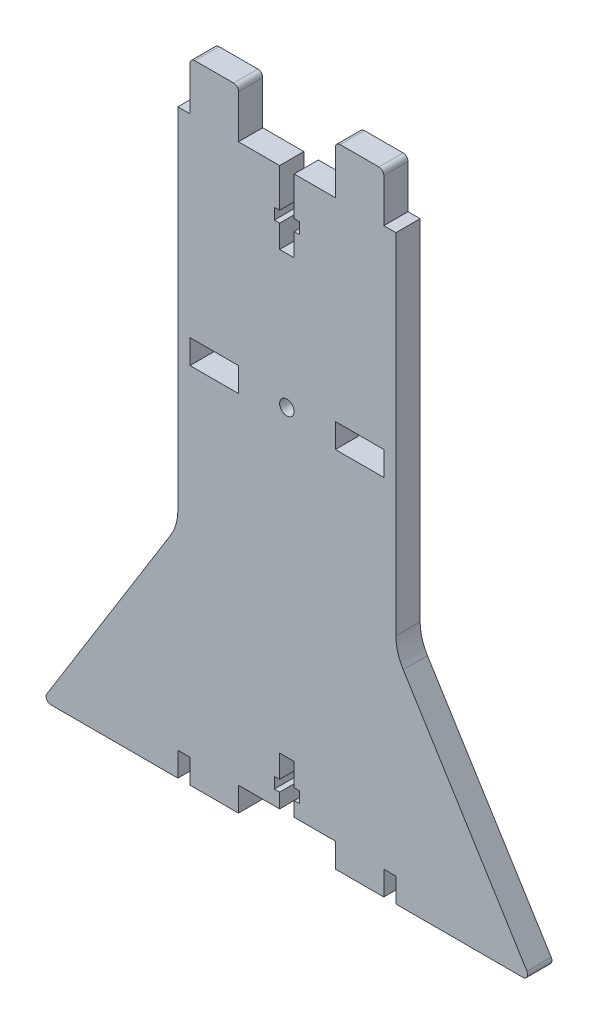
SolidWorks part; units mm, degrees
ref_plane "Front Plane" through (0, 0, 0) normal (0, 0, 1) x (1, 0, 0)
ref_plane "Top Plane" through (0, 0, 0) normal (0, 1, 0) x (1, 0, 0)
ref_plane "Right Plane" through (0, 0, 0) normal (1, 0, 0) x (0, 0, -1)
sketch "Sketch1" plane through (0, 0, 0) normal (0, 0, 1) x (1, 0, 0)
  line L1 (-32.5189, -56.1915) -> (-30.0189, -56.1915)
  line L2 (-30.0189, -56.1915) -> (-30.0189, -61.1915)
  line L3 (-30.0189, -61.1915) -> (-20.0189, -61.1915)
  line L4 (-20.0189, -61.1915) -> (-20.0189, -56.1915)
  line L6 (-0.0189, -56.1915) -> (-0.0189, -61.1915)
  line L7 (-0.0189, -61.1915) -> (9.9811, -61.1915)
  line L8 (9.9811, -61.1915) -> (9.9811, -56.1915)
  line L9 (9.9811, -56.1915) -> (12.4811, -56.1915)
  line L12 (-38.5749, -16.1038) -> (31.2699, -16.1038) construction
  line L13 (-11.5189, -56.1915) -> (-8.5189, -56.1915) construction
  line L14 (-8.5189, -56.1915) -> (-8.5189, -53.1915)
  line L15 (-8.5189, -50.8915) -> (-7.4189, -50.8915)
  line L16 (-12.6189, -53.1915) -> (-12.6189, -50.8915)
  line L17 (-7.4189, -53.1915) -> (-8.5189, -53.1915)
  line L18 (-8.5189, -50.8915) -> (-8.5189, -46.1915)
  line L19 (-8.5189, -46.1915) -> (-11.5189, -46.1915)
  line L20 (-11.5189, -46.1915) -> (-11.5189, -50.8915)
  line L21 (-11.5189, -53.1915) -> (-12.6189, -53.1915)
  line L22 (-7.4189, -50.8915) -> (-7.4189, -53.1915)
  line L23 (-12.6189, -50.8915) -> (-11.5189, -50.8915)
  line L24 (-11.5189, -53.1915) -> (-11.5189, -56.1915)
  line L25 (-10.0189, -46.1915) -> (-10.0189, -56.1915) construction
  line L26 (-11.5189, -56.1915) -> (-20.0189, -56.1915)
  line L27 (-8.5189, -56.1915) -> (-0.0189, -56.1915)
  line L28 (-10.0189, 43.8085) -> (-10.0189, 53.8085) construction
  line L29 (-11.5189, 58.8085) -> (-8.5189, 58.8085) construction
  line L30 (-10.0189, -57.0002) -> (-10.0189, 91.0448) construction
  line L31 (-8.5189, 58.8085) -> (-0.0189, 58.8085)
  line L32 (-11.5189, 58.8085) -> (-20.0189, 58.8085)
  line L33 (-11.5189, 50.8085) -> (-11.5189, 58.8085)
  line L34 (-12.6189, 48.5085) -> (-11.5189, 48.5085)
  line L35 (-7.4189, 48.5085) -> (-7.4189, 50.8085)
  line L36 (-11.5189, 50.8085) -> (-12.6189, 50.8085)
  line L37 (-11.5189, 43.8085) -> (-11.5189, 48.5085)
  line L38 (-8.5189, 43.8085) -> (-11.5189, 43.8085)
  line L39 (-8.5189, 48.5085) -> (-8.5189, 43.8085)
  line L40 (-7.4189, 50.8085) -> (-8.5189, 50.8085)
  line L41 (-12.6189, 50.8085) -> (-12.6189, 48.5085)
  line L42 (-8.5189, 48.5085) -> (-7.4189, 48.5085)
  line L43 (-8.5189, 58.8085) -> (-8.5189, 50.8085)
  line L44 (9.9811, 58.8085) -> (12.4811, 58.8085)
  line L45 (9.9811, 68.8085) -> (9.9811, 58.8085)
  line L46 (-0.0189, 68.8085) -> (9.9811, 68.8085)
  line L47 (-0.0189, 58.8085) -> (-0.0189, 68.8085)
  line L48 (-20.0189, 68.8085) -> (-20.0189, 58.8085)
  line L49 (-30.0189, 68.8085) -> (-20.0189, 68.8085)
  line L50 (-30.0189, 58.8085) -> (-30.0189, 68.8085)
  line L51 (-32.5189, 58.8085) -> (-30.0189, 58.8085)
  line L52 (-32.5189, -56.1915) -> (-32.5189, -61.1915)
  line L53 (-32.5189, -61.1915) -> (-60.5189, -61.1915)
  line L54 (-60.5189, -61.1915) -> (-32.5189, -16.1038)
  line L55 (-32.5189, 58.8085) -> (-32.5189, -16.1038)
  line L56 (12.4811, -56.1915) -> (12.4811, -61.1915)
  line L57 (12.4811, -61.1915) -> (40.4811, -61.1915)
  line L58 (40.4811, -61.1915) -> (12.4811, -16.1038)
  line L59 (12.4811, -16.1038) -> (12.4811, 58.8085)
  point P2 (-0.0189, -58.6915)
  point P57 (-10.0189, 43.8085)
  dimension "D1" = 10
  dimension "D2" = 10
  dimension "D3" = 5
  dimension "D4" = 20
  dimension "D5" = 28
  dimension "D6" = 2.5
  dimension "D7" = 5.2
  dimension "D8" = 3
  dimension "D9" = 2.3
  dimension "D10" = 3
  dimension "D11" = 10
  dimension "D12" = 5
  dimension "D13" = 28
  dimension "D14" = 2.5
  dimension "D15" = 3
  dimension "D16" = 3
  dimension "D17" = 5.2
  dimension "D18" = 45
  dimension "D19" = 10
  dimension "D20" = 20
  dimension "D21" = 22.5
  dimension "D22" = 2.5
  dimension "D24" = 10
  dimension "D25" = 5
  dimension "D26" = 2.5
  dimension "D27" = 10
  dimension "D28" = 53.0745
extrude "Boss-Extrude1" add sketch "Sketch1" along normal blind 5
sketch "Sketch2" plane through (0, 0, 5) normal (0, 0, 1) x (1, 0, 0)
  line L0 (-37.0155, 18.8085) -> (22.4174, 18.8085) construction
  line L2 (-30.0189, 18.8085) -> (-20.0189, 18.8085)
  line L3 (-30.0189, 18.8085) -> (-30.0189, 13.8085)
  line L4 (-30.0189, 13.8085) -> (-20.0189, 13.8085)
  line L5 (-20.0189, 18.8085) -> (-20.0189, 13.8085)
  line L6 (-0.0189, 18.8085) -> (9.9811, 18.8085)
  line L7 (-0.0189, 18.8085) -> (-0.0189, 13.8085)
  line L8 (-0.0189, 13.8085) -> (9.9811, 13.8085)
  line L9 (9.9811, 18.8085) -> (9.9811, 13.8085)
  line L14 (-30.0189, 58.8085) -> (-32.5189, 58.8085) construction
  line L15 (-35.7615, 16.3085) -> (19.4664, 16.3085) construction
  line L16 (-10.0189, 50.0273) -> (-10.0189, 1.4719) construction
  line L17 (-8.5189, 43.8085) -> (-11.5189, 43.8085) construction
  line L21 (-32.5189, 58.8085) -> (-32.5189, -16.1038) construction
  line L22 (12.4811, -16.1038) -> (12.4811, 58.8085) construction
  circle A0 centre (-10.0189, 16.3085) radius 1.5
  point P22 (9.9811, 16.3085)
  point P29 (-10.0189, 43.8085)
  dimension "D2" = 5
  dimension "D3" = 10
  dimension "D1" = 40
  dimension "D4" = 10
  dimension "D5" = 10
  dimension "D6" = 10
  dimension "D7" = 2.5
  dimension "D8" = 2.5
extrude "Cut-Extrude1" cut sketch "Sketch2" against normal blind 10
ref_plane "Plane4" through (12.4811, 58.8085, 5) normal (0, 1, 0) x (1, 0, 0)
fillet "Fillet1" radius 10 2 edges at (12.4811, -16.1038, 2.5) (-32.5189, -16.1038, 2.5)
fillet "Fillet2" radius 1 2 edges at (-60.5189, -61.1915, 2.5) (40.4811, -61.1915, 2.5)
fillet "Congé1" radius 1 4 edges at (-30.0189, 68.8085, 2.5) (-20.0189, 68.8085, 2.5) (-0.0189, 68.8085, 2.5) (9.9811, 68.8085, 2.5)
